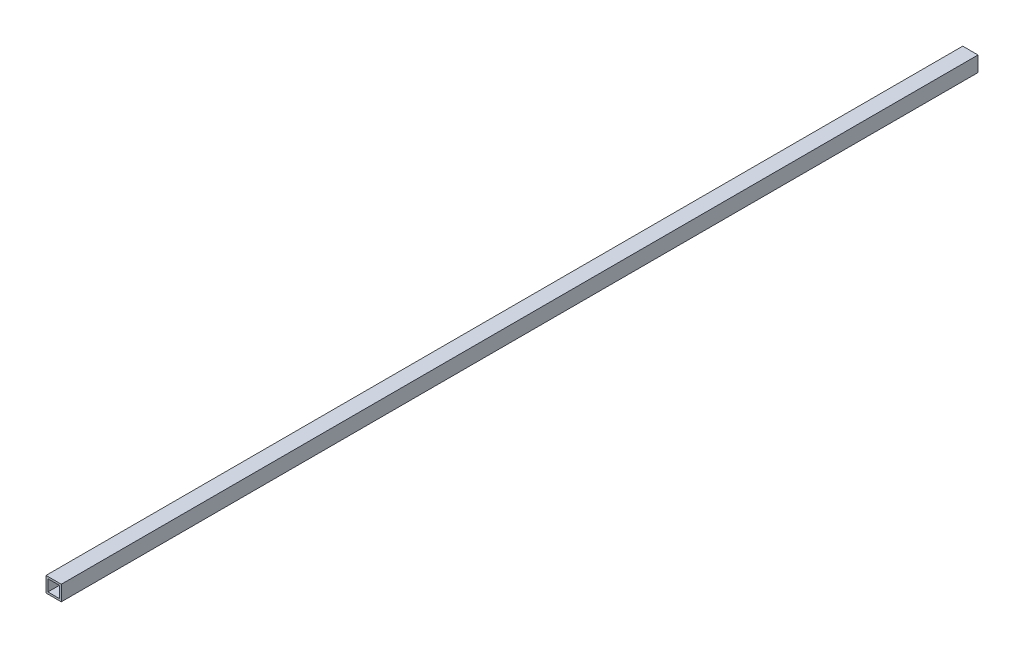
SolidWorks part; units mm, degrees
material "6061-T6 (SS)"
ref_plane "Front Plane" through (0, 0, 0) normal (0, 0, 1) x (1, 0, 0)
ref_plane "Top Plane" through (0, 0, 0) normal (0, 1, 0) x (1, 0, 0)
ref_plane "Right Plane" through (0, 0, 0) normal (1, 0, 0) x (0, 0, -1)
sketch "Sketch1" plane through (0, 0, 0) normal (0, 0, 1) x (1, 0, 0)
  line L0 (330.2, 88.9) -> (317.5, 88.9) construction
  line L1 (317.5, 101.6) -> (317.5, 88.9) construction
  line L2 (330.2, 101.6) -> (317.5, 101.6) construction
  line L3 (330.2, 101.6) -> (330.2, 88.9) construction
  line L4 (330.2, 88.9) -> (317.5, 88.9)
  line L5 (317.5, 101.6) -> (317.5, 88.9)
  line L6 (330.2, 101.6) -> (317.5, 101.6)
  line L7 (330.2, 101.6) -> (330.2, 88.9)
  line L8 (328.6125, 100.0125) -> (319.0875, 100.0125)
  line L9 (319.0875, 100.0125) -> (319.0875, 90.4875)
  line L10 (328.6125, 90.4875) -> (319.0875, 90.4875)
  line L11 (328.6125, 100.0125) -> (328.6125, 90.4875)
  dimension "D1" = 1.5875
extrude "Boss-Extrude1" add sketch "Sketch1" along normal up to vertex (381 mm away) and the other way up to vertex (381 mm away)
